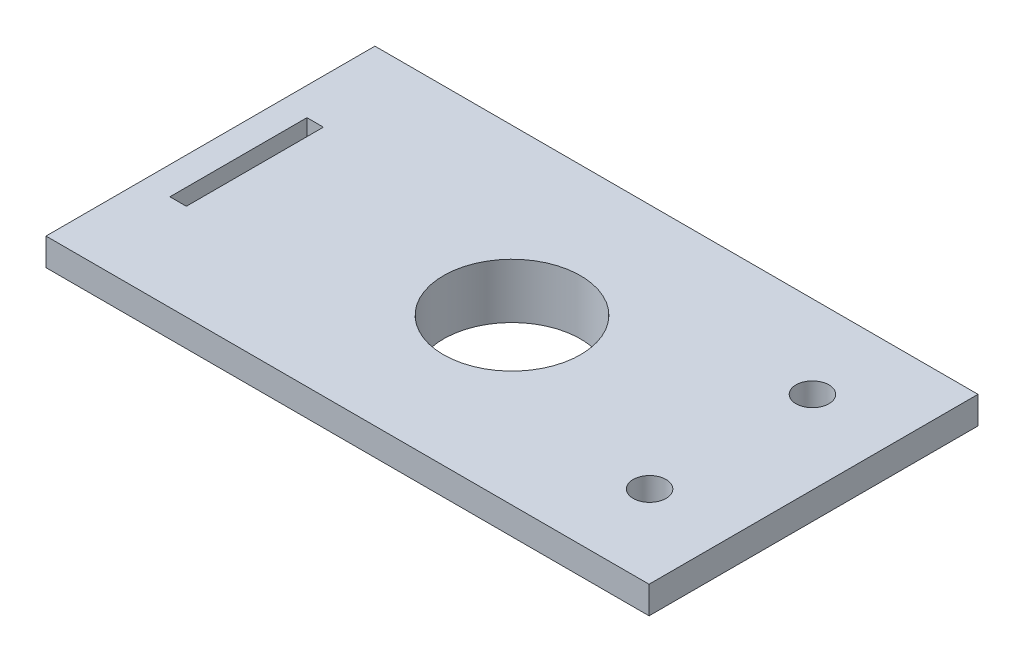
SolidWorks part; units mm, degrees
ref_plane "Front Plane" through (0, 0, 0) normal (0, 0, 1) x (1, 0, 0)
ref_plane "Top Plane" through (0, 0, 0) normal (0, 1, 0) x (1, 0, 0)
ref_plane "Right Plane" through (0, 0, 0) normal (1, 0, 0) x (0, 0, -1)
sketch "Sketch1" plane through (0, 0, 0) normal (0, 1, 0) x (1, 0, 0)
  line L1 (-55, -30) -> (55, -30)
  line L2 (-55, -30) -> (-55, 30)
  line L3 (-55, 30) -> (55, 30)
  line L4 (55, -30) -> (55, 30)
  line L5 (-55, -30) -> (55, 30) construction
  line L6 (-55, 30) -> (55, -30) construction
  point P0 (0, 0)
  dimension "D1" = 110
  dimension "D2" = 60
extrude "Boss-Extrude1" add sketch "Sketch1" along normal blind 5
sketch "Sketch2" plane through (0, 0, 0) normal (0, -1, 0) x (1, 0, 0)
  line L1 (-49.9, -24.9) -> (49.9, -24.9)
  line L2 (-49.9, -24.9) -> (-49.9, 24.9)
  line L3 (-49.9, 24.9) -> (49.9, 24.9)
  line L4 (49.9, -24.9) -> (49.9, 24.9)
  line L5 (-49.9, -24.9) -> (49.9, 24.9) construction
  line L6 (-49.9, 24.9) -> (49.9, -24.9) construction
  point P0 (0, 0)
  dimension "D1" = 99.8
  dimension "D2" = 49.8
extrude "Boss-Extrude2" add sketch "Sketch2" along normal blind 5
sketch "Sketch3" plane through (0, -5, 0) normal (0, -1, 0) x (1, 0, 0)
  line L0 (-49.9, -12.5) -> (-49.9, 12.5)
  line L1 (-49.9, 24.9) -> (-49.9, -24.9) construction
  line L2 (-49.9, -12.5) -> (-46.9, -12.5)
  line L3 (-46.9, -12.5) -> (-46.9, 12.5)
  line L4 (-46.9, 12.5) -> (-49.9, 12.5)
  line L5 (-49.9, 24.9) -> (-49.9, 0) construction
  point P9 (-49.9, 0)
  dimension "D1" = 3
  dimension "D2" = 25
  dimension "D3" = 3
  dimension "D4" = 25
extrude "Cut-Extrude2" cut sketch "Sketch3" against normal blind 10
sketch "Sketch5" plane through (0, -5, 0) normal (0, -1, 0) x (1, 0, 0)
  line L0 (-49.9, -24.9) -> (49.9, -24.9) construction
  line L1 (49.9, 24.9) -> (-49.9, 24.9) construction
  line L2 (49.9, -24.9) -> (49.9, 24.9) construction
  line L3 (55, 30) -> (55, -30) construction
  circle A0 centre (39.9, -14.9) radius 3
  circle A1 centre (40, 14.9) radius 3
  point P10 (0, 0)
  dimension "D1" = 6
  dimension "D5" = 6
  dimension "D2" = 10
  dimension "D3" = 10
  dimension "D4" = 10
  dimension "D6" = 15
  dimension "D7" = 15.1
extrude "Cut-Extrude3" cut sketch "Sketch5" against normal blind 10
sketch "Sketch6" plane through (0, 5, 0) normal (0, 1, 0) x (1, 0, 0)
  circle A0 centre (0, 0) radius 12.5
  dimension "D1" = 25
extrude "Cut-Extrude4" cut sketch "Sketch6" against normal blind 10
